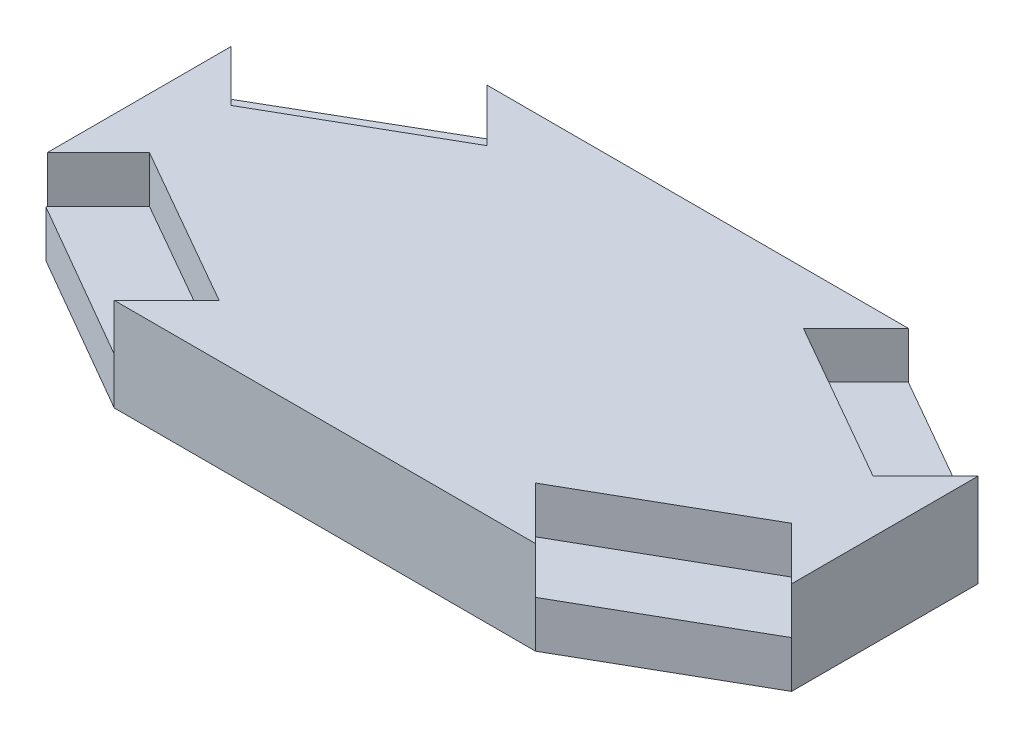
SolidWorks part; units mm, degrees
other "Markup1"
sketch "Sketch4" plane through (50.8, 6.35, 12.7) normal (0.0307, 0.9095, 0.4146) x (0.9597, 0.089, -0.2664)
ref_plane "Front Plane" through (0, 0, 0) normal (0, 0, 1) x (1, 0, 0)
ref_plane "Top Plane" through (0, 0, 0) normal (0, 1, 0) x (1, 0, 0)
ref_plane "Right Plane" through (0, 0, 0) normal (1, 0, 0) x (0, 0, -1)
sketch "Sketch2" plane through (0, 0, 0) normal (0, 1, 0) x (1, 0, 0)
  line L10 (0, 0) -> (50.8, 0) construction
  line L11 (50.8, 6.35) -> (50.8, -6.35)
  line L12 (50.8, -6.35) -> (39.7005, -12.7)
  line L13 (39.7005, -12.7) -> (10.9985, -12.7)
  line L14 (10.9985, -12.7) -> (0, -6.35)
  line L15 (0, -6.35) -> (0, 6.35)
  line L16 (50.8, 6.35) -> (39.7005, 12.7)
  line L17 (39.7005, 12.7) -> (10.9985, 12.7)
  line L18 (10.9985, 12.7) -> (0, 6.35)
  dimension "D1" = 28.702
  dimension "D2" = 50.8
  dimension "D3" = 6.35
  dimension "D4" = 12.7
  dimension "D5" = 12.7
extrude "Boss-Extrude1" add sketch "Sketch2" along normal blind 6.35
sketch "Sketch3" plane through (0, 6.35, 0) normal (0, 1, 0) x (1, 0, 0)
  line L0 (39.7005, -12.7) -> (50.8, -6.35)
  line L1 (39.7005, -12.7) -> (36.1279, -9.1274)
  line L2 (50.8, -6.35) -> (47.2274, -2.7774)
  line L3 (36.1279, -9.1274) -> (47.2274, -2.7774)
  line L4 (0, 0) -> (50.8, 0) construction
  line L5 (50.8, -6.35) -> (50.8, 6.35) construction
  line L6 (25.3495, 12.7) -> (25.3495, -12.7) construction
  line L7 (39.7005, 12.7) -> (10.9985, 12.7) construction
  line L8 (10.9985, -12.7) -> (39.7005, -12.7) construction
  line L9 (-0.101, -6.35) -> (3.4717, -2.7774)
  line L10 (14.5712, -9.1274) -> (3.4717, -2.7774)
  line L11 (10.9985, -12.7) -> (14.5712, -9.1274)
  line L12 (10.9985, -12.7) -> (-0.101, -6.35)
  line L13 (50.8, 6.35) -> (47.2274, 2.7774)
  line L14 (36.1279, 9.1274) -> (47.2274, 2.7774)
  line L15 (39.7005, 12.7) -> (36.1279, 9.1274)
  line L16 (39.7005, 12.7) -> (50.8, 6.35)
  line L17 (10.9985, 12.7) -> (-0.101, 6.35)
  line L18 (10.9985, 12.7) -> (14.5712, 9.1274)
  line L19 (14.5712, 9.1274) -> (3.4717, 2.7774)
  line L20 (-0.101, 6.35) -> (3.4717, 2.7774)
  dimension "D1" = 5.0525
  dimension "D2" = 45
extrude "Cut-Extrude1" cut sketch "Sketch3" against normal blind 3.175
